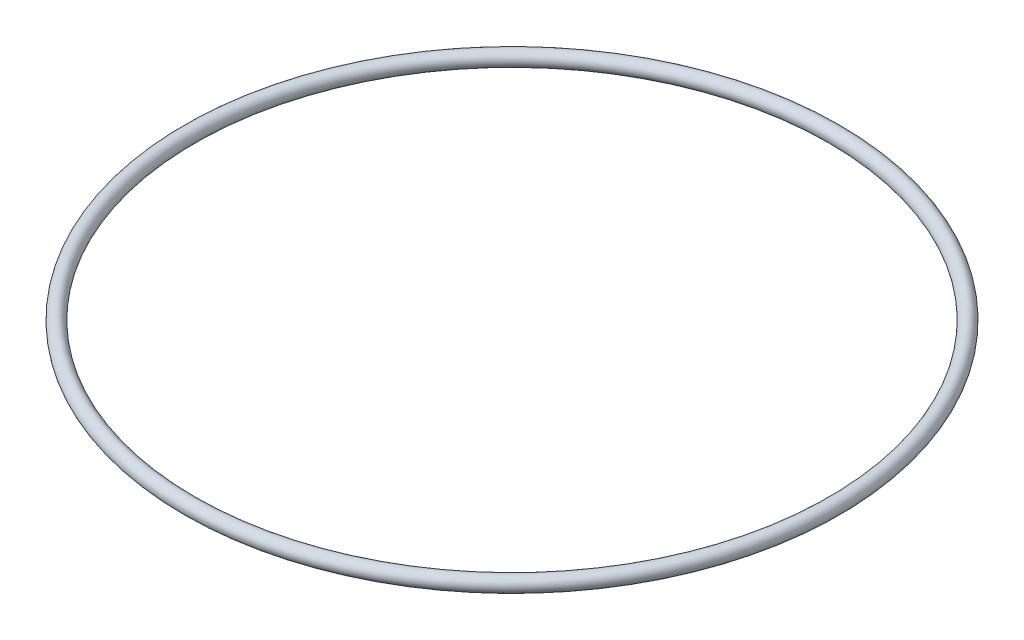
SolidWorks part; units mm, degrees
ref_plane "Płaszczyzna przednia" through (0, 0, 0) normal (0, 0, 1) x (1, 0, 0)
ref_plane "Płaszczyzna górna" through (0, 0, 0) normal (0, 1, 0) x (1, 0, 0)
ref_plane "Płaszczyzna prawa" through (0, 0, 0) normal (1, 0, 0) x (0, 0, -1)
sketch "Szkic1" plane through (0, 0, 0) normal (0, 0, 1) x (1, 0, 0)
  line L0 (0, 5.5368) -> (0, -8.229) construction
  circle A0 centre (-65.5, 0) radius 1.5
  dimension "D1" = 3
  dimension "D2" = 65.5
revolve "Obrót1" add sketch "Szkic1" angle 360 about L0
